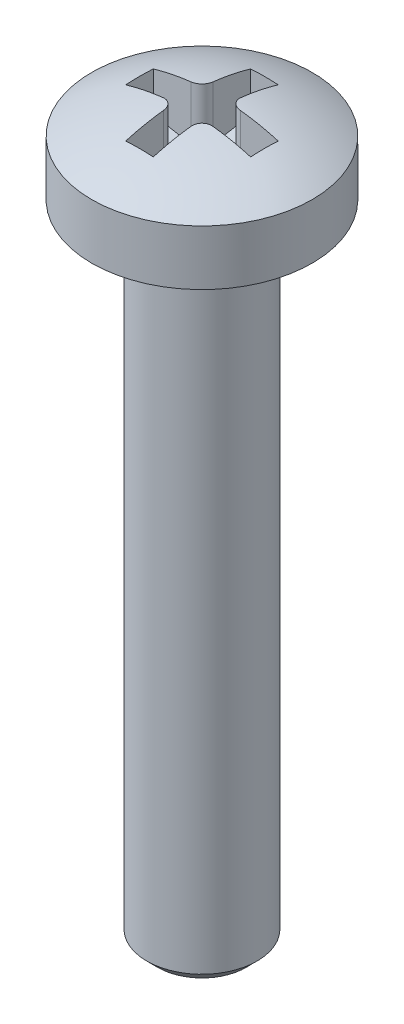
SolidWorks part; units mm, degrees
material "Cast Stainless Steel"
ref_plane "Front Plane" through (0, 0, 0) normal (0, 0, 1) x (1, 0, 0)
ref_plane "Top Plane" through (0, 0, 0) normal (0, 1, 0) x (1, 0, 0)
ref_plane "Right Plane" through (0, 0, 0) normal (1, 0, 0) x (0, 0, -1)
sketch "Sketch1" plane through (0, 0, 0) normal (0, 0, 1) x (1, 0, 0)
  line L0 (0, 0) -> (0, 4.6)
  line L1 (0, 4.6) -> (0, -22.0705) construction
  line L2 (6, 3) -> (6, 0)
  line L3 (6, 0) -> (3, 0)
  line L4 (3, 0) -> (3, -35)
  line L5 (3, -35) -> (0, -35)
  line L6 (0, -35) -> (0, 0)
  arc A0 (0, 4.6) -> (6, 3) centre (0, -7.45) cw
  dimension "D2" = 6
  dimension "D3" = 12
  dimension "D1" = 3
  dimension "D4" = 4.6
  dimension "D5" = 35
revolve "Revolve1" add sketch "Sketch1" angle 360 about L1
sketch "Sketch3" plane through (0, 0, 0) normal (0, 0, 1) x (1, 0, 0)
  line L0 (6, 1.5) -> (-6, 1.5) construction
  line L1 (6, 0) -> (6, 3) construction
  line L2 (-6, 3) -> (-6, 0) construction
  line L3 (0, 0) -> (0, 1.5) construction
  arc A0 (0, 1.5) -> (6, 3) centre (0, 14.25) ccw
  point P3 (0, 1.5)
surface "Surface-Revolve1" sketch "Sketch3" parameters "D1"=360
sketch "Sketch4" plane through (0, 0, 0) normal (0, 1, 0) x (1, 0, 0)
  line L0 (-0.75, -0.75) -> (-0.75, -3.4)
  line L1 (-3.4, 0.75) -> (-0.75, 0.75)
  line L2 (-3.4, 0.75) -> (-3.4, -0.75)
  line L3 (-3.4, -0.75) -> (-0.75, -0.75)
  line L4 (3.4, 0.75) -> (3.4, -0.75)
  line L5 (-3.4, 0.75) -> (3.4, -0.75) construction
  line L6 (-3.4, -0.75) -> (3.4, 0.75) construction
  line L7 (-0.75, 3.4) -> (0.75, 3.4)
  line L8 (-0.75, 3.4) -> (-0.75, 0.75)
  line L9 (-0.75, -3.4) -> (0.75, -3.4)
  line L10 (0.75, 3.4) -> (0.75, 0.75)
  line L11 (-0.75, 3.4) -> (0.75, -3.4) construction
  line L12 (-0.75, -3.4) -> (0.75, 3.4) construction
  line L13 (0.75, 0.75) -> (3.4, 0.75)
  line L14 (0.75, -0.75) -> (0.75, -3.4)
  line L15 (0.75, -0.75) -> (3.4, -0.75)
  point P0 (0, 0)
  point P6 (0, 0)
  dimension "D3" = 1.5
  dimension "D4" = 1.5
  dimension "D1" = 6.8
  dimension "D2" = 6.8
extrude "Cut-Extrude1" cut sketch "Sketch4" against normal up to surface (18.0154 mm away) from offset 20
delete or keep bodies "Body-Delete/Keep 1" type delete bodies bodies 102
fillet "Fillet1" radius 0.6 4 edges at (0.75, 3.0487, -0.75) (0.75, 3.0487, 0.75) (-0.75, 3.0487, 0.75) (-0.75, 3.0487, -0.75)
chamfer "Chamfer1" distance 0.6 angle 45 1 edges at (0, -35, 3)
equation "\"d1\" = 6"
equation "\"d2\" = \"d1\" * 2"
equation "\"k\" = 4.6"
equation "\"v\" = 3"
equation "\"D1@Sketch1\"=\"v\""
equation "\"D3@Sketch1\"=\"d2\""
equation "\"D2@Sketch1\"= \"d1\""
equation "\"D4@Sketch1\"=\"k\""
equation "\"L\" = 35"
equation "\"D5@Sketch1\"=\"L\""
equation "\"D1@Sketch4\"=\"m\""
equation "\"D2@Sketch4\"=\"m\""
equation "\"D3@Sketch4\" = \"d1\" / 4"
equation "\"D4@Sketch4\" = \"d1\" / 4"
equation "\"D1@Fillet1\"=\"d1\"/10"
equation "\"D1@Chamfer1\"=\"d1\"/10"
equation "\"m\"= 6.8"
